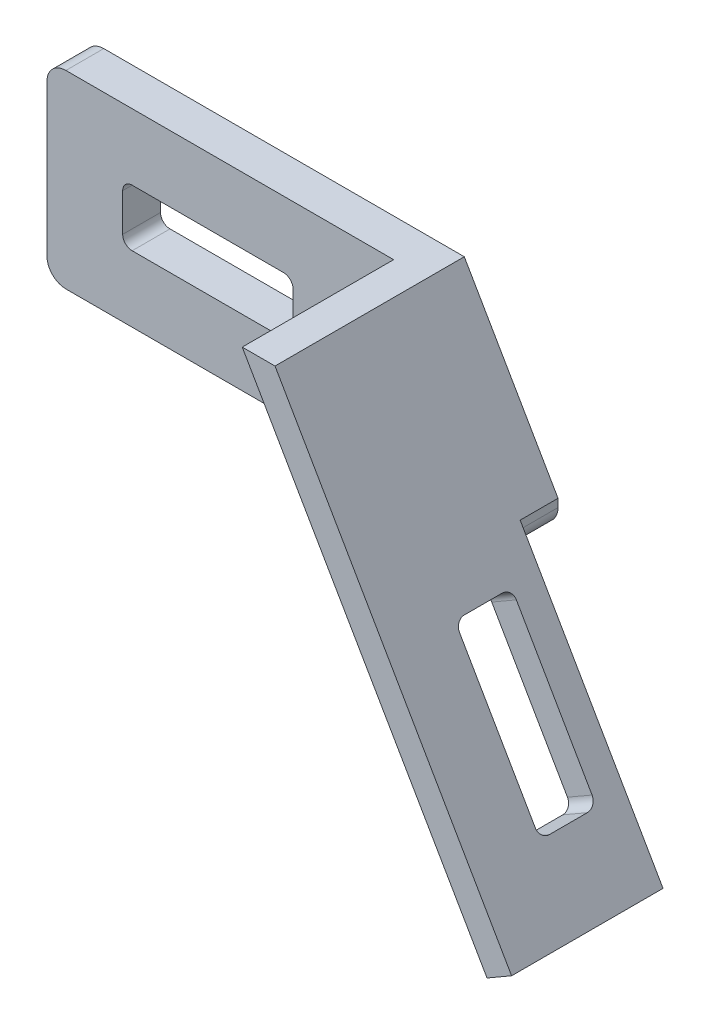
SolidWorks part; units mm, degrees
ref_plane "Plan de face" through (0, 0, 0) normal (0, 0, 1) x (1, 0, 0)
ref_plane "Plan de dessus" through (0, 0, 0) normal (0, 1, 0) x (1, 0, 0)
ref_plane "Plan de droite" through (0, 0, 0) normal (1, 0, 0) x (0, 0, -1)
sketch "Esquisse1" plane through (0, 0, 0) normal (0, 0, 1) x (1, 0, 0)
  line L1 (-11.2733, 8.7087) -> (34.7267, 8.7087)
  line L2 (-13.2733, 6.7087) -> (-13.2733, -9.2913)
  line L3 (-11.2733, -11.2913) -> (34.7267, -11.2913)
  line L4 (36.7267, 6.7087) -> (36.7267, -9.2913)
  arc A0 (34.7267, 8.7087) -> (36.7267, 6.7087) centre (34.7267, 6.7087) cw
  arc A1 (36.7267, -9.2913) -> (34.7267, -11.2913) centre (34.7267, -9.2913) cw
  arc A2 (-11.2733, -11.2913) -> (-13.2733, -9.2913) centre (-11.2733, -9.2913) cw
  arc A3 (-13.2733, 6.7087) -> (-11.2733, 8.7087) centre (-11.2733, 6.7087) cw
  point P8 (36.7267, -11.2913)
  point P11 (-13.2733, -11.2913)
  point P14 (-13.2733, 8.7087)
  dimension "D3" = 2
  dimension "D1" = 20
  dimension "D2" = 50
extrude "Boss.-Extru.1" add sketch "Esquisse1" along normal blind 4
sketch "Esquisse3" plane through (0, 0, 4) normal (0, 0, 1) x (1, 0, 0)
  line L0 (-13.2733, 6.7087) -> (-13.2733, -9.2913) construction
  line L1 (-4.2733, 1.7087) -> (11.7267, 1.7087)
  line L2 (-5.2733, 0.7087) -> (-5.2733, -3.2913)
  line L3 (-4.2733, -4.2913) -> (11.7267, -4.2913)
  line L4 (12.7267, 0.7087) -> (12.7267, -3.2913)
  line L5 (-5.2733, 1.7087) -> (12.7267, -4.2913) construction
  line L6 (-5.2733, -4.2913) -> (12.7267, 1.7087) construction
  line L7 (-11.2733, -11.2913) -> (34.7267, -11.2913) construction
  line L8 (34.7267, 8.7087) -> (-11.2733, 8.7087) construction
  arc A0 (-5.2733, 0.7087) -> (-4.2733, 1.7087) centre (-4.2733, 0.7087) cw
  arc A1 (-5.2733, -3.2913) -> (-4.2733, -4.2913) centre (-4.2733, -3.2913) ccw
  arc A2 (11.7267, -4.2913) -> (12.7267, -3.2913) centre (11.7267, -3.2913) ccw
  arc A3 (12.7267, 0.7087) -> (11.7267, 1.7087) centre (11.7267, 0.7087) ccw
  point P0 (3.7267, -1.2913)
  dimension "D4" = 1
  dimension "D1" = 18
  dimension "D2" = 6
  dimension "D3" = 8
  dimension "D5" = 7
  dimension "D6" = 7
extrude "Enlèv. mat.-Extru.1" cut sketch "Esquisse3" against normal blind 50
sketch "Esquisse4" plane through (0, 0, 4) normal (0, 0, 1) x (1, 0, 0)
  line L0 (27.4007, 7.7087) -> (51.8233, -34.5926)
  line L1 (34.7267, 8.7087) -> (-11.2733, 8.7087) construction
  line L2 (51.8233, -34.5926) -> (49.2253, -36.0926)
  line L3 (49.2253, -36.0926) -> (23.3592, 8.7087)
  line L4 (23.3592, 8.7087) -> (25.6686, 8.7087)
  line L6 (-11.2733, -11.2913) -> (34.7267, -11.2913) construction
  line L7 (25.6686, 8.7087) -> (26.8233, 8.7087)
  line L8 (26.8233, 8.7087) -> (27.4007, 7.7087)
  point P11 (26.8233, 8.7087)
  dimension "D1" = 50
  dimension "D2" = 3
  dimension "D3" = 60
extrude "Boss.-Extru.2" add sketch "Esquisse4" along normal blind 16
sketch "Esquisse6" plane through (21.2904, 12.292, 0) normal (-0.866, -0.5, 0) x (0, 0, 1)
  line L1 (8, -29.8697) -> (12, -29.8697)
  line L2 (7, -30.8697) -> (7, -46.8697)
  line L3 (8, -47.8697) -> (12, -47.8697)
  line L4 (13, -30.8697) -> (13, -46.8697)
  line L5 (7, -29.8697) -> (13, -47.8697) construction
  line L6 (7, -47.8697) -> (13, -29.8697) construction
  line L8 (20, -55.8697) -> (4, -55.8697) construction
  line L9 (4, -27.2228) -> (4, -55.8697) construction
  arc A0 (12, -29.8697) -> (13, -30.8697) centre (12, -30.8697) cw
  arc A1 (8, -29.8697) -> (7, -30.8697) centre (8, -30.8697) ccw
  arc A2 (7, -46.8697) -> (8, -47.8697) centre (8, -46.8697) ccw
  arc A3 (12, -47.8697) -> (13, -46.8697) centre (12, -46.8697) ccw
  point P0 (10, -38.8697)
  dimension "D5" = 1
  dimension "D6" = 1
  dimension "D7" = 1
  dimension "D8" = 1
  dimension "D1" = 6
  dimension "D2" = 8
  dimension "D3" = 18
  dimension "D4" = 3
extrude "Enlèv. mat.-Extru.2" cut sketch "Esquisse6" against normal up to next
sketch "Esquisse11" plane through (0, 0, 4) normal (0, 0, 1) x (1, 0, 0)
  line L1 (36.7494, 6.7946) -> (36.9916, -8.9032)
  line L2 (36.9916, -8.9032) -> (27.4007, 7.7087)
  line L7 (51.8233, -34.5926) -> (26.8233, 8.7087) construction
  line L8 (27.4007, 7.7087) -> (26.8233, 8.7087)
  line L11 (26.8233, 8.7087) -> (34.7267, 8.7087)
  arc A1 (34.7267, 8.7087) -> (36.7494, 6.7946) centre (35.5934, 7.5987) cw
extrude "Enlèv. mat.-Extru.4" cut sketch "Esquisse11" against normal through all
